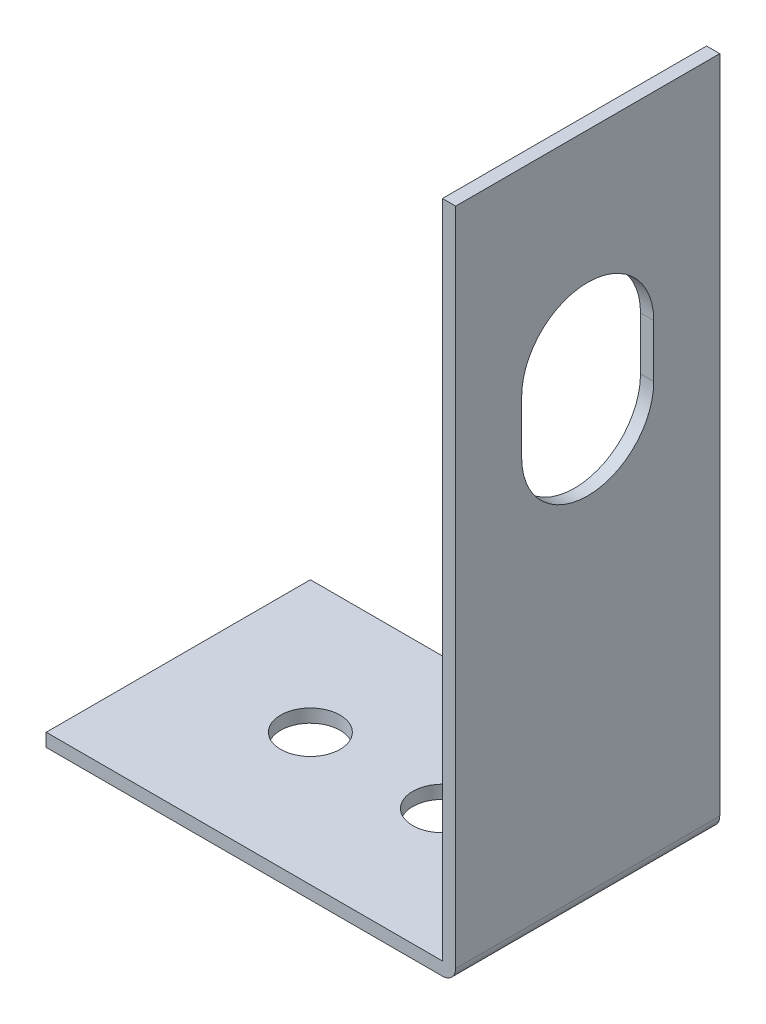
SolidWorks part; units mm, degrees
ref_plane "Plan de face" through (0, 0, 0) normal (0, 0, 1) x (1, 0, 0)
ref_plane "Plan de dessus" through (0, 0, 0) normal (0, 1, 0) x (1, 0, 0)
ref_plane "Plan de droite" through (0, 0, 0) normal (1, 0, 0) x (0, 0, -1)
sketch "Esquisse1" plane through (0, 0, 0) normal (0, 0, 1) x (1, 0, 0)
  line L0 (0, 0) -> (0, 50)
  line L1 (0, 0) -> (-30, 0)
  line L2 (0, -1) -> (-30, -1)
  line L3 (1, 0) -> (1, 50)
  line L4 (0, 50) -> (1, 50)
  line L5 (-30, 0) -> (-30, -1)
  line L6 (1, -1) -> (-30, -1) construction
  line L7 (1, -1) -> (1, 50) construction
  arc A0 (0, -1) -> (1, 0) centre (0, 0) ccw
  dimension "D4" = 1
  dimension "D1" = 50
  dimension "D2" = 30
  dimension "D3" = 1
extrude "Extrusion1" add sketch "Esquisse1" along normal blind 20
sketch "Esquisse2" plane through (0, 0, 0) normal (-1, 0, 0) x (0, 0, 1)
  line L0 (10, 50) -> (10, 0) construction
  line L1 (20, 50) -> (0, 50) construction
  line L2 (20, 0) -> (0, 0) construction
  line L3 (5, 35) -> (5, 31)
  line L4 (15, 35) -> (15, 31)
  arc A0 (15, 35) -> (5, 35) centre (10, 35) ccw
  arc A1 (5, 31) -> (15, 31) centre (10, 31) ccw
  dimension "D1" = 5
  dimension "D2" = 15
  dimension "D3" = 4
extrude "Enlèv. mat.-Extru.1" cut sketch "Esquisse2" against normal through all
sketch "Esquisse3" plane through (0, 0, 0) normal (0, 1, 0) x (-1, 0, 0)
  line L0 (0, 10) -> (30, 10) construction
  line L1 (0, 20) -> (0, 0) construction
  line L2 (30, 20) -> (30, 0) construction
  circle A0 centre (10, 10) radius 2.25
  circle A1 centre (20, 10) radius 2.25
  dimension "D1" = 4.5
  dimension "D2" = 10
  dimension "D3" = 10
extrude "Enlèv. mat.-Extru.2" cut sketch "Esquisse3" against normal through all
